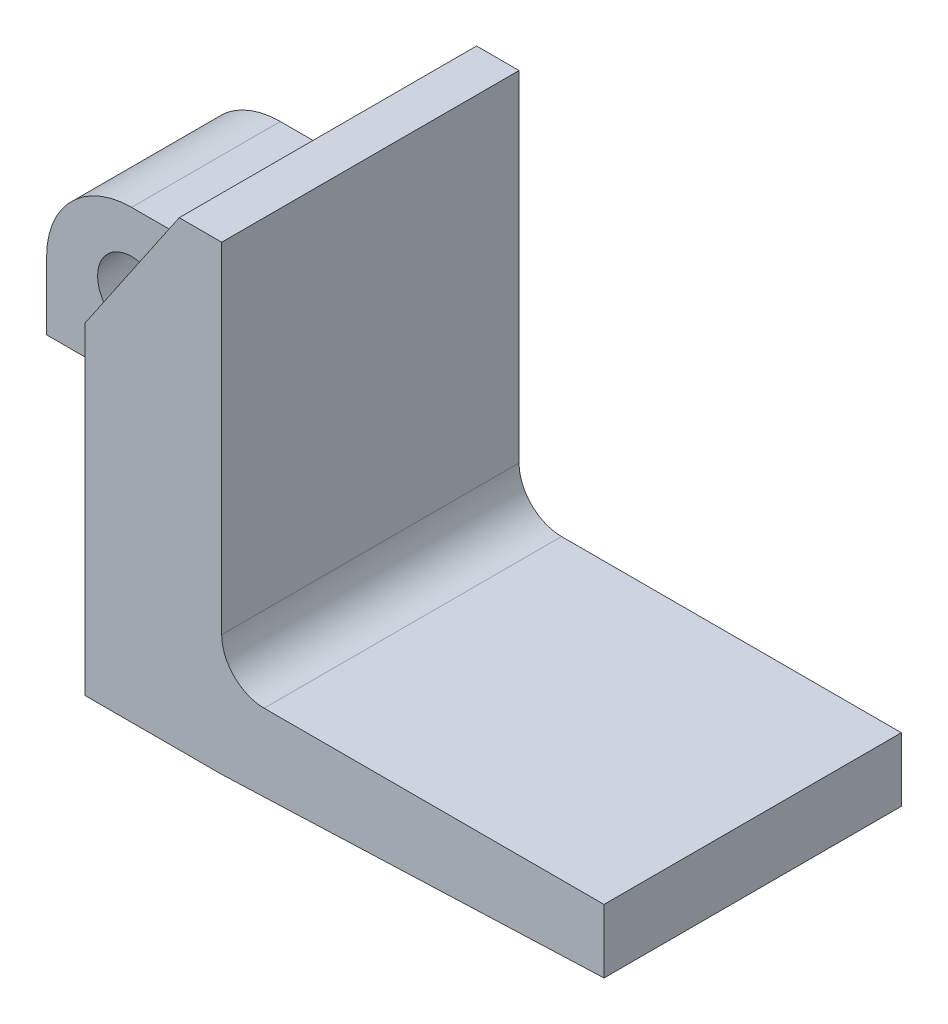
SolidWorks part; units mm, degrees
material "7075-T6 (SN)"
ref_plane "Front Plane" through (0, 0, 0) normal (0, 0, 1) x (1, 0, 0)
ref_plane "Top Plane" through (0, 0, 0) normal (0, 1, 0) x (1, 0, 0)
ref_plane "Right Plane" through (0, 0, 0) normal (1, 0, 0) x (0, 0, -1)
sketch "Sketch1" plane through (0, 0, 0) normal (0, 0, 1) x (1, 0, 0)
  line L0 (0, 0) -> (57.15, 0)
  line L1 (57.15, 0) -> (57.15, -9.525)
  line L2 (-20.4502, 9.8455) -> (-48.3902, 9.8455)
  line L3 (-48.3902, 9.8455) -> (-48.3902, 20.0055)
  line L7 (0, 57.15) -> (0, 0)
  line L8 (-20.4502, 9.8455) -> (-20.4502, -11.7445)
  line L13 (-35.6902, 32.7055) -> (-22.9902, 32.7055)
  line L15 (-22.9902, 32.7055) -> (-6.35, 57.15)
  line L16 (-6.35, 57.15) -> (0, 57.15)
  line L17 (-20.4502, -11.7445) -> (0, -11.7445)
  line L18 (0, -11.7445) -> (57.15, -9.525)
  arc A0 (-35.6902, 32.7055) -> (-48.3902, 20.0055) centre (-35.6902, 20.0055) ccw
  dimension "D5" = 12.7
  dimension "D1" = 57.15
  dimension "D2" = 22.86
  dimension "D3" = 9.525
  dimension "D4" = 35.6902
  dimension "D6" = 9.8455
  dimension "D7" = 25.4
  dimension "D8" = 12.7
  dimension "D9" = 21.59
  dimension "D10" = 10.16
  dimension "D11" = 57.15
  dimension "D12" = 6.35
  dimension "D13" = 27.94
extrude "Boss-Extrude1" add sketch "Sketch1" along normal blind 44.45
fillet "Fillet2" radius 6.35 1 edges at (0, 0, 22.225)
sketch "Sketch3" plane through (0, 0, 44.45) normal (0, 0, 1) x (1, 0, 0)
  line L0 (-48.3902, 9.8455) -> (-20.4502, 9.8455) construction
  line L1 (-48.3902, 20.0055) -> (-48.3902, 9.8455) construction
  line L2 (-22.9902, 32.7055) -> (-35.6902, 32.7055) construction
  line L3 (-48.3902, 9.8455) -> (-20.4502, 9.8455)
  line L4 (-48.3902, 20.0055) -> (-48.3902, 9.8455)
  line L5 (-22.9902, 32.7055) -> (-35.6902, 32.7055)
  line L7 (-20.4502, 9.8455) -> (-20.4502, 36.4368)
  line L8 (-6.35, 57.15) -> (-22.9902, 32.7055) construction
  line L9 (-20.4502, 36.4368) -> (-22.9902, 32.7055)
  arc A0 (-35.6902, 32.7055) -> (-48.3902, 20.0055) centre (-35.6902, 20.0055) ccw construction
  arc A1 (-35.6902, 32.7055) -> (-48.3902, 20.0055) centre (-35.6902, 20.0055) ccw
extrude "Cut-Extrude1" cut sketch "Sketch3" against normal blind 22.225
fillet "Fillet3" radius 2.54 1 edges at (-22.9902, 32.7055, 11.1125)
sketch "Sketch6" plane through (0, 0, 0) normal (0, 0, -1) x (-1, 0, 0)
  line L0 (48.3902, 20.0055) -> (48.3902, 9.8455) construction
  line L1 (48.3902, 9.8455) -> (20.4502, 9.8455) construction
  point P0 (35.6902, 21.2755)
  dimension "D1" = 12.7
  dimension "D2" = 11.43
hole_wizard "3/8 (0.375) Diameter Hole1" positions "Sketch6" profile "Sketch5" hole size "3/8" standard "ANSI Inch" end condition through all
sketch "Sketch5" plane through (-35.6902, 21.2755, 0) normal (1, 0, 0) x (0, 1, 0)
  line L0 (0, 0) -> (0, 44.45)
  line L1 (0, 44.45) -> (5.08, 44.45)
  line L2 (5.08, 44.45) -> (5.08, 0)
  line L5 (5.08, 0) -> (0, 0)
  line L11 (0, -6.35) -> (0, 107.95) construction
  dimension "Thru Hole Dia." = 10.16
  dimension "Thru Hole Depth" = 44.45
